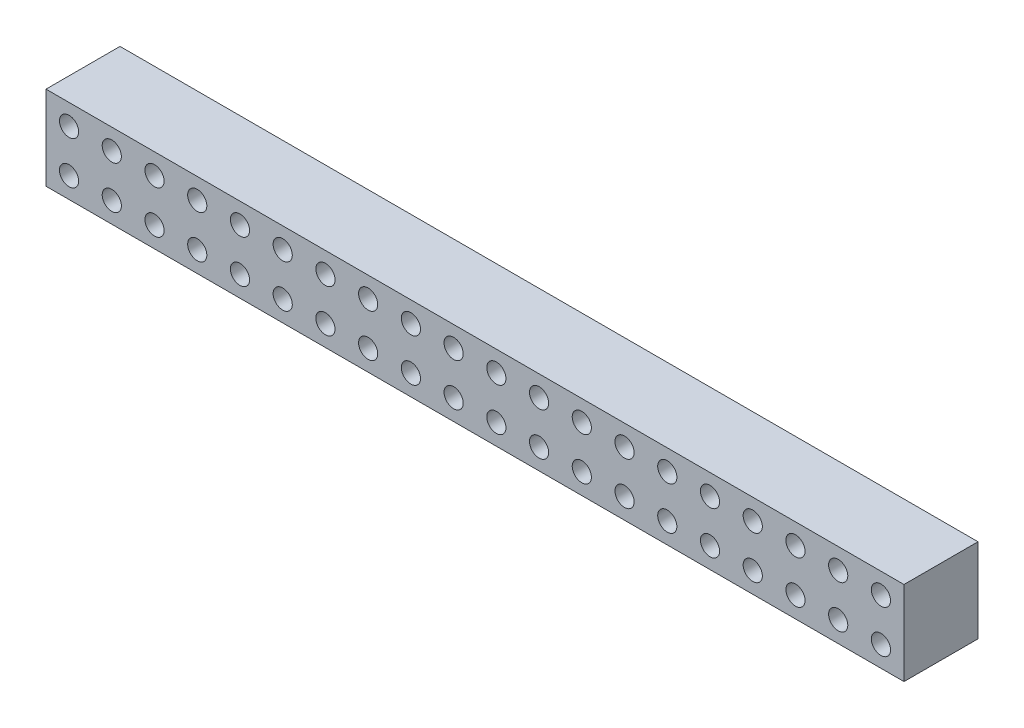
SolidWorks part; units mm, degrees
ref_plane "Alzado" through (0, 0, 0) normal (0, 0, 1) x (1, 0, 0)
ref_plane "Planta" through (0, 0, 0) normal (0, 1, 0) x (1, 0, 0)
ref_plane "Vista lateral" through (0, 0, 0) normal (1, 0, 0) x (0, 0, -1)
sketch "Croquis1" plane through (0, 0, 0) normal (0, 0, 1) x (1, 0, 0)
  line L1 (25.5, -2.5) -> (-25.5, -2.5)
  line L2 (25.5, -2.5) -> (25.5, 2.5)
  line L3 (25.5, 2.5) -> (-25.5, 2.5)
  line L4 (-25.5, -2.5) -> (-25.5, 2.5)
  line L5 (25.5, -2.5) -> (-25.5, 2.5) construction
  line L6 (25.5, 2.5) -> (-25.5, -2.5) construction
  point P0 (0, 0)
  dimension "D1" = 51
  dimension "D2" = 5
extrude "Saliente-Extruir1" add sketch "Croquis1" along normal blind 4.4
sketch "Croquis2" plane through (0, 0, 4.4) normal (0, 0, 1) x (1, 0, 0)
  line L0 (-1.27, 1.27) -> (1.27, -1.27) construction
  circle A0 centre (-24.13, 1.27) radius 0.57
  circle A1 centre (-21.59, 1.27) radius 0.57
  circle A2 centre (-19.05, 1.27) radius 0.57
  circle A3 centre (-16.51, 1.27) radius 0.57
  circle A4 centre (-13.97, 1.27) radius 0.57
  circle A5 centre (-11.43, 1.27) radius 0.57
  circle A6 centre (-8.89, 1.27) radius 0.57
  circle A7 centre (-6.35, 1.27) radius 0.57
  circle A8 centre (-3.81, 1.27) radius 0.57
  circle A9 centre (-1.27, 1.27) radius 0.57
  circle A10 centre (1.27, 1.27) radius 0.57
  circle A11 centre (3.81, 1.27) radius 0.57
  circle A12 centre (6.35, 1.27) radius 0.57
  circle A13 centre (8.89, 1.27) radius 0.57
  circle A14 centre (11.43, 1.27) radius 0.57
  circle A15 centre (13.97, 1.27) radius 0.57
  circle A16 centre (16.51, 1.27) radius 0.57
  circle A17 centre (19.05, 1.27) radius 0.57
  circle A18 centre (21.59, 1.27) radius 0.57
  circle A19 centre (24.13, 1.27) radius 0.57
  circle A20 centre (-21.59, -1.27) radius 0.57
  circle A21 centre (-19.05, -1.27) radius 0.57
  circle A22 centre (-16.51, -1.27) radius 0.57
  circle A23 centre (-13.97, -1.27) radius 0.57
  circle A24 centre (-11.43, -1.27) radius 0.57
  circle A25 centre (-8.89, -1.27) radius 0.57
  circle A26 centre (-6.35, -1.27) radius 0.57
  circle A27 centre (-3.81, -1.27) radius 0.57
  circle A28 centre (-1.27, -1.27) radius 0.57
  circle A29 centre (1.27, -1.27) radius 0.57
  circle A30 centre (3.81, -1.27) radius 0.57
  circle A31 centre (6.35, -1.27) radius 0.57
  circle A32 centre (8.89, -1.27) radius 0.57
  circle A33 centre (11.43, -1.27) radius 0.57
  circle A34 centre (13.97, -1.27) radius 0.57
  circle A35 centre (16.51, -1.27) radius 0.57
  circle A36 centre (19.05, -1.27) radius 0.57
  circle A37 centre (21.59, -1.27) radius 0.57
  circle A38 centre (24.13, -1.27) radius 0.57
  circle A39 centre (-24.13, -1.27) radius 0.57
  point P2 (0, 0)
  point P3 (-24.2823, 0.9877)
  point P4 (-23.6872, 1.1903)
  dimension "D1" = 1.14
  dimension "D4" = 2.54
  dimension "D5" = 2.54
  dimension "D2" = 20
  dimension "D3" = 2
extrude "Cortar-Extruir1" cut sketch "Croquis2" against normal through all
